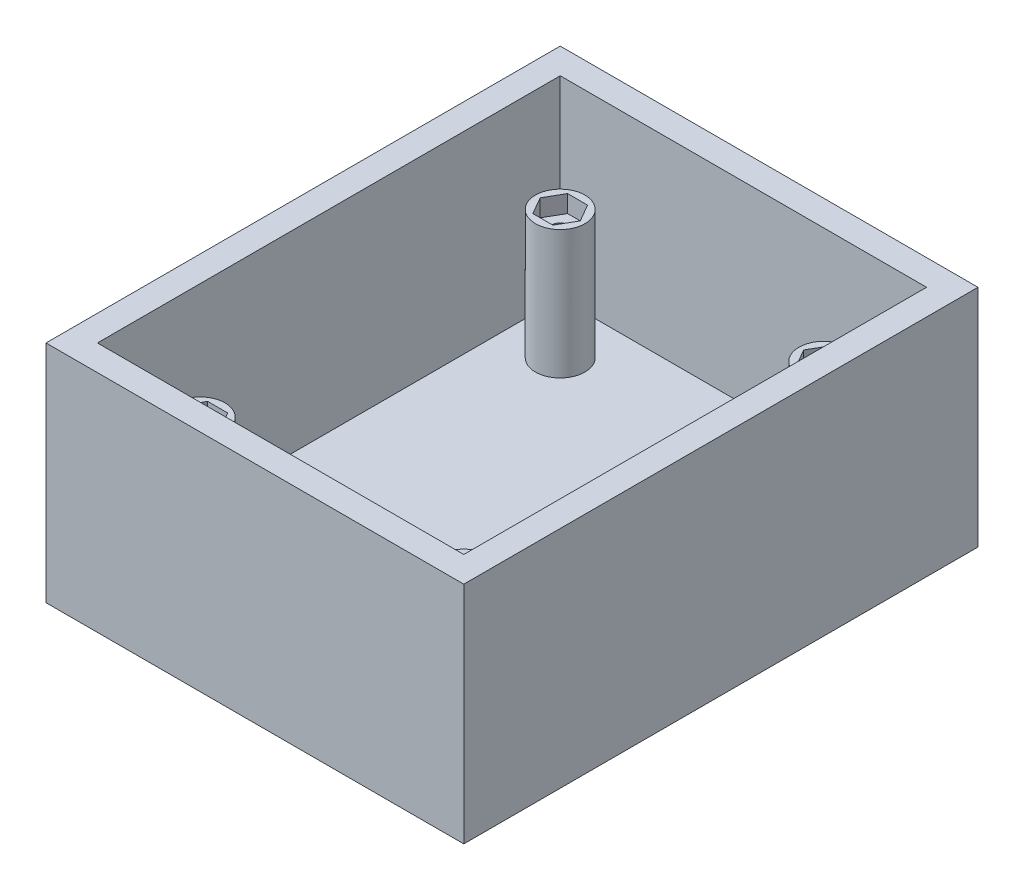
SolidWorks part; units mm, degrees
ref_plane "Front Plane" through (0, 0, 0) normal (0, 0, 1) x (1, 0, 0)
ref_plane "Top Plane" through (0, 0, 0) normal (0, 1, 0) x (1, 0, 0)
ref_plane "Right Plane" through (0, 0, 0) normal (1, 0, 0) x (0, 0, -1)
sketch "Sketch1" plane through (0, 0, 0) normal (0, 1, 0) x (1, 0, 0)
  line L0 (-32.5, 40) -> (32.5, -40) construction
  line L1 (-32.5, -40) -> (32.5, -40)
  line L2 (-32.5, -40) -> (-32.5, 40)
  line L3 (-32.5, 40) -> (32.5, 40)
  line L4 (32.5, -40) -> (32.5, 40)
  line L5 (32.5, 40) -> (-32.5, -40) construction
  point P4 (0, 0)
  dimension "D1" = 65
  dimension "D2" = 80
extrude "Boss-Extrude1" add sketch "Sketch1" along normal blind 5
sketch "Sketch2" plane through (0, 5, 0) normal (0, 1, 0) x (1, 0, 0)
  line L0 (-28.5, 36) -> (28.5, -36) construction
  line L1 (-28.5, -36) -> (28.5, -36)
  line L2 (-28.5, -36) -> (-28.5, 36)
  line L3 (-28.5, 36) -> (28.5, 36)
  line L4 (28.5, -36) -> (28.5, 36)
  line L5 (28.5, 36) -> (-28.5, -36) construction
  line L7 (-32.5, -40) -> (32.5, -40)
  line L8 (-32.5, -40) -> (-32.5, 40)
  line L9 (-32.5, 40) -> (32.5, 40)
  line L10 (32.5, -40) -> (32.5, 40)
  point P4 (0, 0)
  dimension "D1" = 72
  dimension "D2" = 57
extrude "Boss-Extrude2" add sketch "Sketch2" along normal blind 30
sketch "Sketch3" plane through (0, 5, 0) normal (0, 1, 0) x (1, 0, 0)
  line L0 (-28.5, 36) -> (-28.5, -36) construction
  line L1 (-23.5, -31) -> (23.5, -31) construction
  line L2 (-23.5, -31) -> (-23.5, 31) construction
  line L3 (-23.5, 31) -> (23.5, 31) construction
  line L4 (23.5, -31) -> (23.5, 31) construction
  line L5 (-23.5, -31) -> (23.5, 31) construction
  line L6 (-23.5, 31) -> (23.5, -31) construction
  line L7 (28.5, -36) -> (28.5, 36) construction
  line L8 (-28.5, -36) -> (28.5, -36) construction
  line L9 (28.5, 36) -> (-28.5, 36) construction
  circle A0 centre (-20.5, -28) radius 3.85
  circle A1 centre (20.5, -28) radius 3.85
  circle A2 centre (20.5, 28) radius 3.85
  circle A3 centre (-20.5, 28) radius 3.85
  point P4 (0, 0)
  dimension "D5" = 7.7
  dimension "D8" = 7.7
  dimension "D13" = 7.7
  dimension "D16" = 7.7
  dimension "D1" = 5
  dimension "D2" = 5
  dimension "D3" = 5
  dimension "D4" = 5
  dimension "D6" = 3
  dimension "D7" = 3
  dimension "D9" = 3
  dimension "D10" = 3
  dimension "D11" = 3
  dimension "D12" = 3
  dimension "D14" = 3
  dimension "D15" = 3
extrude "Boss-Extrude3" add sketch "Sketch3" along normal blind 20
hole_wizard "Tap Drill for M3 Tap1" positions "Sketch6" profile "Sketch5" hole size "M3" standard "ISO"
sketch "Sketch6" plane through (0, 25, 0) normal (0, 1, 0) x (1, 0, 0)
  point P0 (-20.5, 28)
  point P3 (20.5, 28)
  point P6 (20.5, -28)
  point P9 (-20.5, -28)
sketch "Sketch5" plane through (-20.5, 25, -28) normal (1, 0, 0) x (0, 0, 1)
  line L0 (0, 0) -> (0, 12.7511)
  line L1 (0, 12.7511) -> (1.25, 12)
  line L2 (1.25, 12) -> (1.25, 0)
  line L5 (1.25, 0) -> (0, 0)
  line L10 (0, 12.7511) -> (-1.25, 12) construction
  line L11 (0, -6.35) -> (0, 107.95) construction
  dimension "Hole Dia." = 2.5
  dimension "Hole Depth" = 12
  dimension "Drill Angle" = 118
sketch "Sketch8" plane through (0, 25, 0) normal (0, 1, 0) x (1, 0, 0)
  line L1 (-17.3823, 28) -> (-18.9412, 30.7)
  line L2 (-18.9412, 30.7) -> (-22.0588, 30.7)
  line L3 (-22.0588, 30.7) -> (-23.6177, 28)
  line L4 (-23.6177, 28) -> (-22.0588, 25.3)
  line L5 (-22.0588, 25.3) -> (-18.9412, 25.3)
  line L6 (-18.9412, 25.3) -> (-17.3823, 28)
  circle A0 centre (-20.5, 28) radius 2.7 construction
  circle A1 centre (-20.5, 28) radius 1.25 construction
  point P11 (0, 0)
  dimension "D1" = 2.7
  dimension "D2" = 3.1177
extrude "Cut-Extrude1" cut sketch "Sketch8" against normal blind 2.7
mirror "Mirror1" about plane through (0, 0, 0) normal (0, 0, 1) of "Cut-Extrude1" second plane through (0, 0, 0) second plane normal (1, 0, 0)
